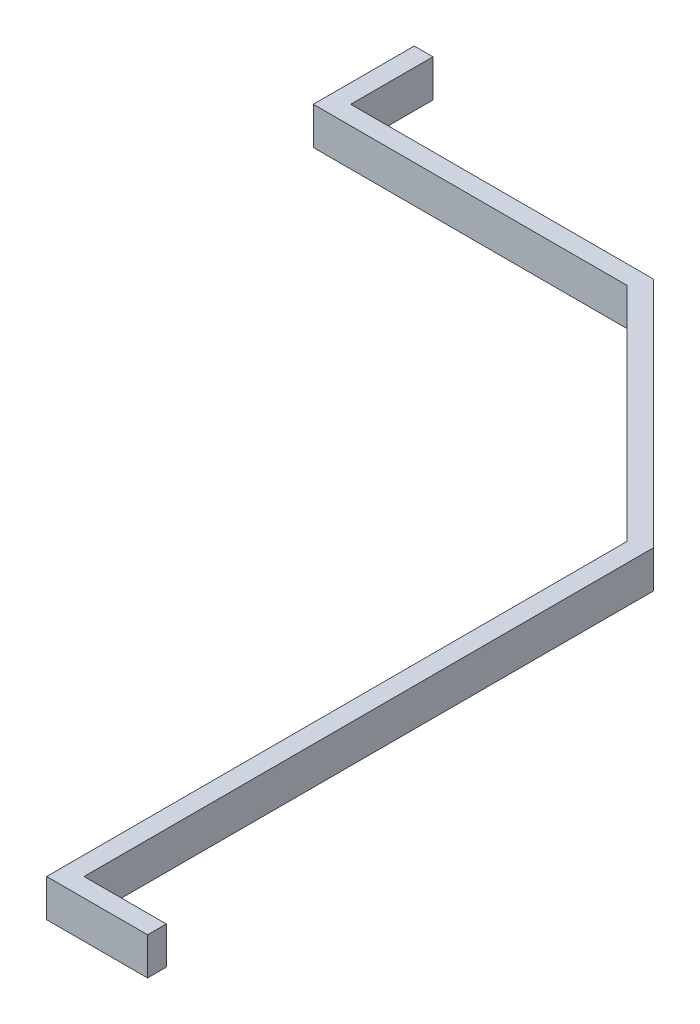
SolidWorks part; units mm, degrees
ref_plane "Front Plane" through (0, 0, 0) normal (0, 0, 1) x (1, 0, 0)
ref_plane "Top Plane" through (0, 0, 0) normal (0, 1, 0) x (1, 0, 0)
ref_plane "Right Plane" through (0, 0, 0) normal (1, 0, 0) x (0, 0, -1)
sketch "Sketch1" plane through (0, 0, 0) normal (0, 1, 0) x (1, 0, 0)
  line L0 (0, 0) -> (0, 772.708)
  line L1 (0, 772.708) -> (-315.9819, 1088.6899)
  line L2 (-315.9819, 1088.6899) -> (-726.7399, 1088.6899)
  line L3 (-726.7399, 1088.6899) -> (-726.7399, 1200.2899)
  line L4 (-726.7399, 1200.2899) -> (-752.1399, 1200.2899)
  line L5 (-752.1399, 1200.2899) -> (-752.1399, 1063.2899)
  line L6 (-752.1399, 1063.2899) -> (-326.5029, 1063.2899)
  line L7 (-326.5029, 1063.2899) -> (-25.4, 762.1869)
  line L8 (-25.4, 762.1869) -> (-25.4, -25.4)
  line L9 (-25.4, -25.4) -> (111.6, -25.4)
  line L10 (111.6, -25.4) -> (111.6, 0)
  line L11 (111.6, 0) -> (0, 0)
  line L12 (-175.9515, 912.7384) -> (-157.991, 930.6989) construction
  line L13 (-726.7399, 1088.6899) -> (-726.7399, 1063.2899) construction
  line L14 (0, 390.8552) -> (-25.4, 390.8552) construction
  line L15 (-122.0699, 966.6199) -> (-157.991, 930.6989) construction
  line L20 (50.8, 793.75) -> (57.8711, 800.8211)
  line L21 (50.8, 793.75) -> (-294.9399, 1139.4899)
  line L22 (-294.9399, 1139.4899) -> (-287.8688, 1146.5609)
  line L23 (57.8711, 800.8211) -> (-287.8688, 1146.5609)
  line L24 (-294.9399, 1149.4899) -> (-726.7399, 1149.4899)
  line L25 (-294.9399, 1149.4899) -> (-294.9399, 1139.4899)
  line L26 (-294.9399, 1139.4899) -> (-726.7399, 1139.4899)
  line L27 (-726.7399, 1149.4899) -> (-726.7399, 1139.4899)
  line L28 (50.8, 793.75) -> (60.8, 793.75)
  line L29 (50.8, 793.75) -> (50.8, 0)
  line L30 (50.8, 0) -> (60.8, 0)
  line L31 (60.8, 793.75) -> (60.8, 0)
  line L32 (50.8, 396.875) -> (0, 396.875) construction
  line L33 (-510.8399, 1139.4899) -> (-510.8399, 1088.6899) construction
  point P22 (55.8, 0)
  point P28 (55.8, 0)
  point P30 (-726.7399, 1144.4899)
  point P31 (-726.7399, 1144.4899)
  dimension "D2" = 793.75
  dimension "D3" = 488.95
  dimension "D4" = 431.8
  dimension "D5" = 10
  dimension "D6" = 25.4
  dimension "D7" = 50.8
extrude "Boss-Extrude1" add sketch "Sketch1" along normal blind 50.8 contours L4 L5 L6 L7 L8 L9 L10 L11 L0 L1 L2 L3
